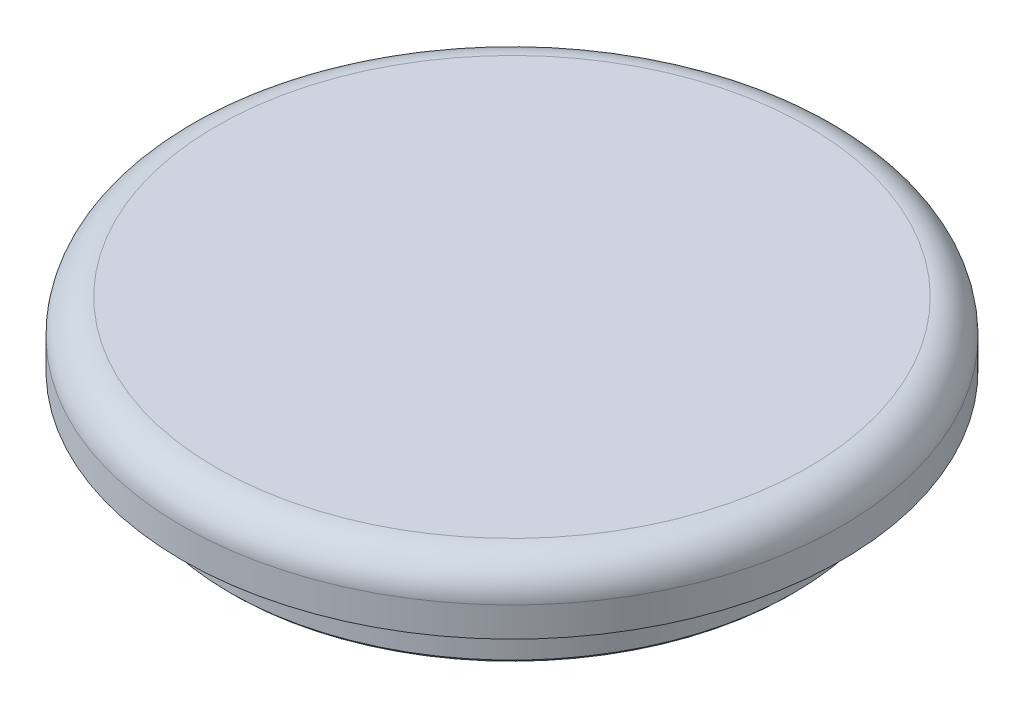
SolidWorks part; units mm, degrees
material "6061 Alloy"
ref_plane "Front Plane" through (0, 0, 0) normal (0, 0, 1) x (1, 0, 0)
ref_plane "Top Plane" through (0, 0, 0) normal (0, 1, 0) x (1, 0, 0)
ref_plane "Right Plane" through (0, 0, 0) normal (1, 0, 0) x (0, 0, -1)
sketch "Sketch1" plane through (0, 0, 0) normal (0, 1, 0) x (1, 0, 0)
  circle A0 centre (0, 0) radius 49.53
  circle A1 centre (0, 0) radius 49.53 construction
extrude " body" add sketch "Sketch1" along normal blind 9.525
sketch "Sketch2" plane through (0, 0, 0) normal (0, -1, 0) x (1, 0, 0)
  circle A0 centre (0, 0) radius 42.4265
  circle A1 centre (0, 0) radius 36.0765
  circle A2 centre (0, 0) radius 42.6805 construction
  circle A5 centre (0, 0) radius 42.6805 construction
  dimension "D1" = 0.254
  dimension "D2" = 6.35
extrude "flange" add sketch "Sketch2" along normal blind 8.255
fillet "Fillet1" radius 5.08 1 edges at (0, 9.525, 49.53)
chamfer "Chamfer1" distance 0.508 angle 45 2 edges at (0, -8.255, -36.0765) (0, -8.255, -42.4265)
